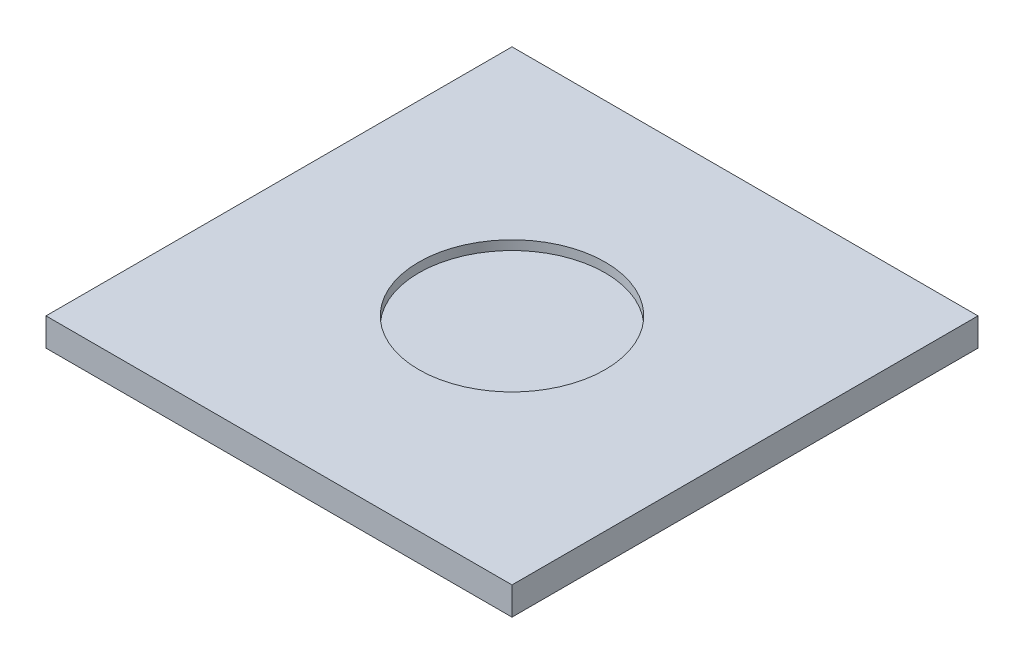
SolidWorks part; units mm, degrees
material "Pine"
ref_plane "Front Plane" through (0, 0, 0) normal (0, 0, 1) x (1, 0, 0)
ref_plane "Top Plane" through (0, 0, 0) normal (0, 1, 0) x (1, 0, 0)
ref_plane "Right Plane" through (0, 0, 0) normal (1, 0, 0) x (0, 0, -1)
sketch "Sketch1" plane through (0, 0, 0) normal (0, 1, 0) x (1, 0, 0)
  line L1 (-125, 125) -> (125, 125)
  line L2 (-125, 125) -> (-125, -125)
  line L3 (-125, -125) -> (125, -125)
  line L4 (125, 125) -> (125, -125)
  line L5 (-125, 125) -> (125, -125) construction
  line L6 (-125, -125) -> (125, 125) construction
  point P0 (0, 0)
extrude "Boss-Extrude1" add sketch "Sketch1" along normal blind 15
sketch "Sketch2" plane through (0, 15, 0) normal (0, 1, 0) x (1, 0, 0)
  circle A0 centre (0, 0) radius 50
extrude "Cut-Extrude1" cut sketch "Sketch2" against normal blind 5
